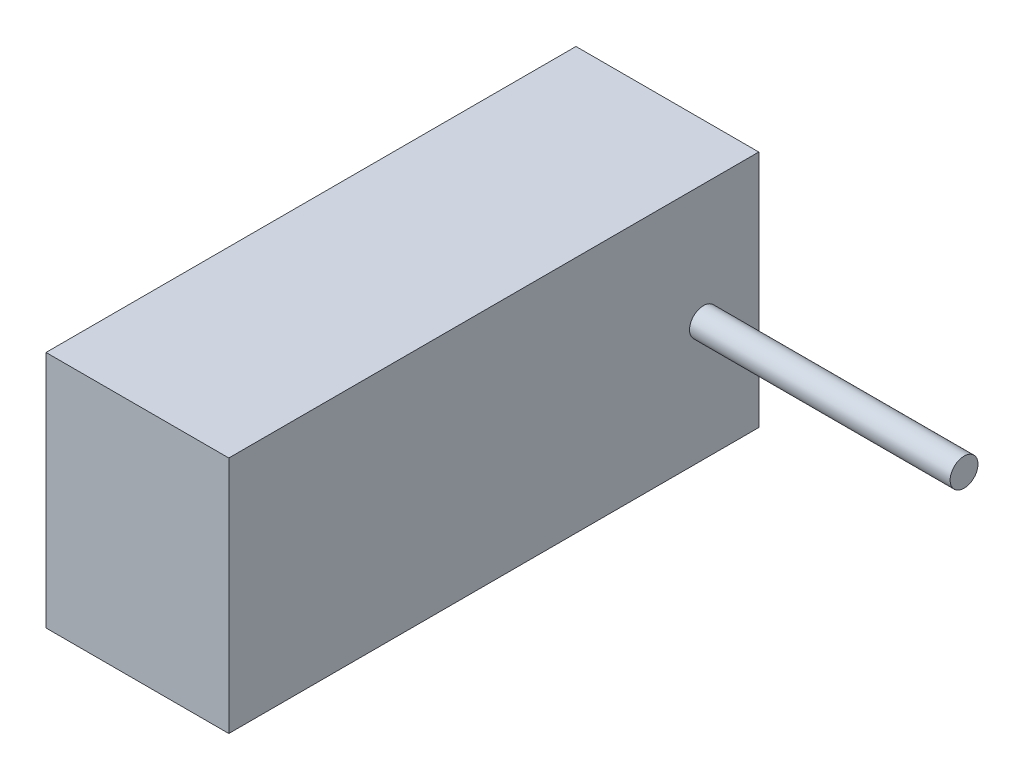
SolidWorks part; units mm, degrees
ref_plane "Plan de face" through (0, 0, 0) normal (0, 0, 1) x (1, 0, 0)
ref_plane "Plan de dessus" through (0, 0, 0) normal (0, 1, 0) x (1, 0, 0)
ref_plane "Plan de droite" through (0, 0, 0) normal (1, 0, 0) x (0, 0, -1)
sketch "Esquisse1" plane through (0, 0, 0) normal (0, 1, 0) x (1, 0, 0)
  line L0 (0, 0) -> (19.15, 0)
  line L1 (0, 0) -> (0, 55.52)
  line L2 (0, 55.52) -> (19.15, 55.52)
  line L3 (19.15, 55.52) -> (19.15, 0)
extrude "Boss.-Extru.1" add sketch "Esquisse1" along normal blind 25 contours L1 L2 L3 L0
sketch "Esquisse3" plane through (0, 0, 0) normal (1, 0, 0) x (0, 0, -1)
  circle A0 centre (49.7267, 12.5) radius 1.46
extrude "Boss.-Extru.2" add sketch "Esquisse3" along normal blind 46.45 contours A0
